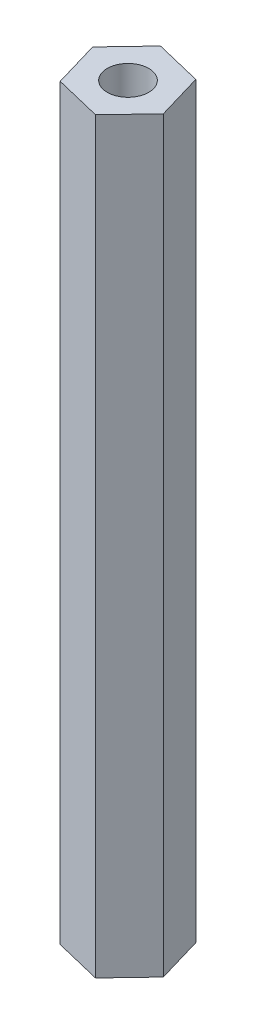
SolidWorks part; units mm, degrees
material "Thornel VCB-20 Carbon Cloth"
ref_plane "Front Plane" through (0, 0, 0) normal (0, 0, 1) x (1, 0, 0)
ref_plane "Top Plane" through (0, 0, 0) normal (0, 1, 0) x (1, 0, 0)
ref_plane "Right Plane" through (0, 0, 0) normal (1, 0, 0) x (0, 0, -1)
sketch "Sketch1" plane through (0, 0, 0) normal (0, 1, 0) x (1, 0, 0)
  line L1 (0.9773, -3.3234) -> (3.3668, -0.8153)
  line L2 (3.3668, -0.8153) -> (2.3895, 2.508)
  line L3 (2.3895, 2.508) -> (-0.9773, 3.3234)
  line L4 (-0.9773, 3.3234) -> (-3.3668, 0.8153)
  line L5 (-3.3668, 0.8153) -> (-2.3895, -2.508)
  line L6 (-2.3895, -2.508) -> (0.9773, -3.3234)
  circle A0 centre (0, 0) radius 1.5
  circle A1 centre (0, 0) radius 3 construction
  dimension "D1" = 3
  dimension "D2" = 6
extrude "Boss-Extrude1" add sketch "Sketch1" along normal mid plane 54
